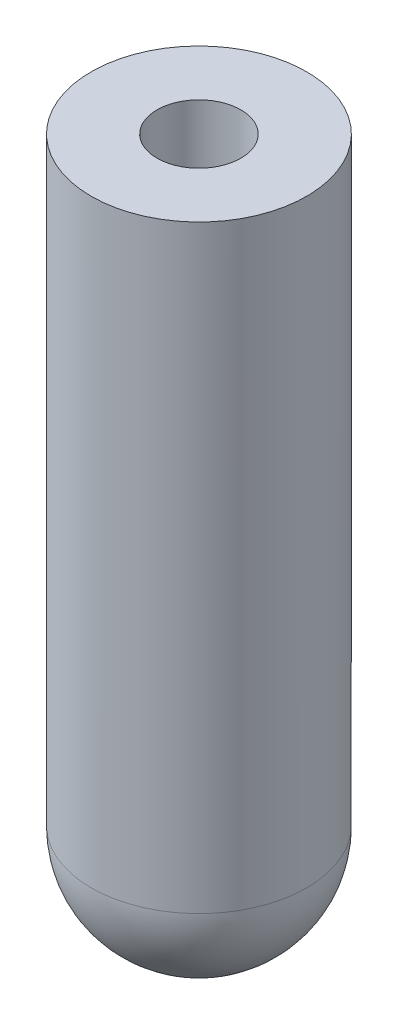
SolidWorks part; units mm, degrees
material "Silicon Rubber"
ref_plane "Front" through (0, 0, 0) normal (0, 0, 1) x (1, 0, 0)
ref_plane "Top" through (0, 0, 0) normal (0, 1, 0) x (1, 0, 0)
ref_plane "Right" through (0, 0, 0) normal (1, 0, 0) x (0, 0, -1)
sketch "Sketch1" plane through (0, 0, 0) normal (0, 1, 0) x (1, 0, 0)
  circle A0 centre (0, 0) radius 9
  circle A1 centre (0, 0) radius 3.5
  dimension "D1" = 7
  dimension "D2" = 18
extrude "Boss-Extrude1" add sketch "Sketch1" against normal blind 50
ref_plane "Plane1" through (0, -50, 0) normal (0, -1, 0) x (-1, 0, 0)
sketch "Sketch2" plane through (0, -50, 0) normal (0, -1, 0) x (-1, 0, 0)
  line L0 (0, -9) -> (0, 9) construction
  line L1 (0, -9) -> (0, 9)
  circle A0 centre (0, 0) radius 9 construction
  arc A1 (0, 9) -> (0, -9) centre (0, 0) ccw
revolve "Revolve1" add sketch "Sketch2" angle 180 about L0
